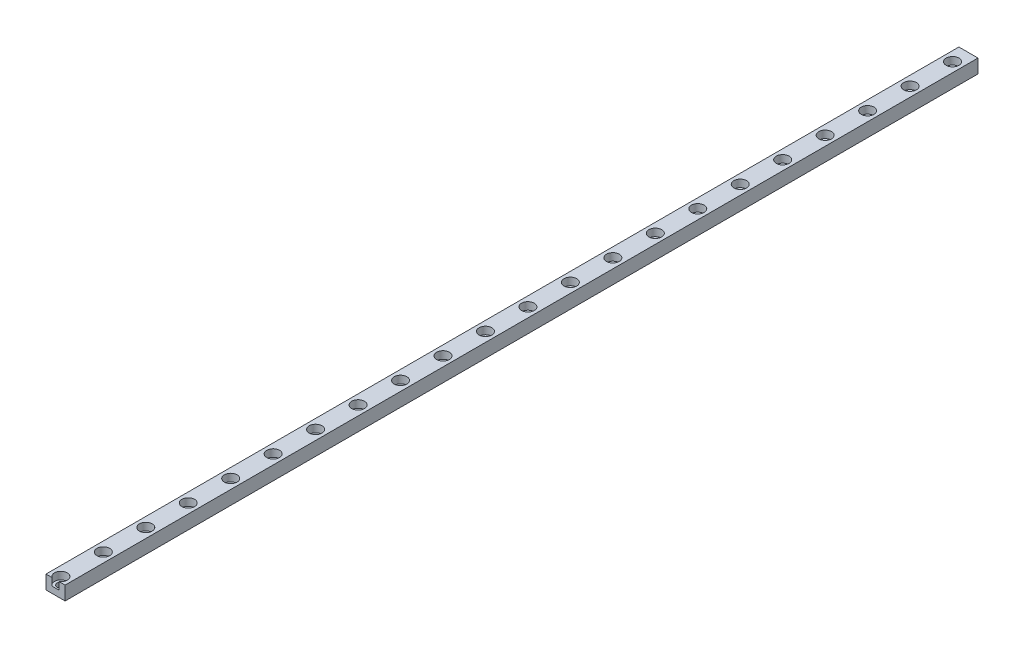
SolidWorks part; units mm, degrees
material "AISI 304"
ref_plane "前视基准面" through (0, 0, 0) normal (0, 0, 1) x (1, 0, 0)
ref_plane "上视基准面" through (0, 0, 0) normal (0, 1, 0) x (1, 0, 0)
ref_plane "右视基准面" through (0, 0, 0) normal (1, 0, 0) x (0, 0, -1)
sketch "草图1" plane through (0, 0, -89.2648) normal (0, 0, 1) x (1, 0, 0)
  line L1 (-4.5, -3.25) -> (4.5, -3.25)
  line L2 (-4.5, -3.25) -> (-4.5, 3.25)
  line L3 (-4.5, 3.25) -> (4.5, 3.25)
  line L4 (4.5, -3.25) -> (4.5, 3.25)
  line L5 (-4.5, -3.25) -> (4.5, 3.25) construction
  line L6 (-4.5, 3.25) -> (4.5, -3.25) construction
  point P0 (0, 0)
  dimension "D1" = 9
  dimension "D2" = 6.5
extrude "凸台-拉伸1" add sketch "草图1" along normal blind 430
sketch "草图2" plane through (0, 3.25, 0) normal (0, 1, 0) x (1, 0, 0)
  line L0 (0, 0) -> (0, -499.5684) construction
  line L1 (4.5, 89.2648) -> (-4.5, 89.2648) construction
  circle A0 centre (0, 81.7648) radius 1.75
  circle A1 centre (0, 61.7648) radius 1.75
  circle A2 centre (0, 41.7648) radius 1.75
  circle A3 centre (0, 21.7648) radius 1.75
  circle A4 centre (0, 1.7648) radius 1.75
  circle A5 centre (0, -18.2352) radius 1.75
  circle A6 centre (0, -38.2352) radius 1.75
  circle A7 centre (0, -58.2352) radius 1.75
  circle A8 centre (0, -78.2352) radius 1.75
  circle A9 centre (0, -98.2352) radius 1.75
  circle A10 centre (0, -118.2352) radius 1.75
  circle A11 centre (0, -138.2352) radius 1.75
  circle A12 centre (0, -158.2352) radius 1.75
  circle A13 centre (0, -178.2352) radius 1.75
  circle A14 centre (0, -198.2352) radius 1.75
  circle A15 centre (0, -218.2352) radius 1.75
  circle A16 centre (0, -238.2352) radius 1.75
  circle A17 centre (0, -258.2352) radius 1.75
  circle A18 centre (0, -278.2352) radius 1.75
  circle A19 centre (0, -298.2352) radius 1.75
  circle A20 centre (0, -318.2352) radius 1.75
  circle A21 centre (0, -338.2352) radius 1.75
  circle A22 centre (0, -358.2352) radius 1.75
  circle A23 centre (0, -378.2352) radius 1.75
  circle A24 centre (0, -398.2352) radius 1.75
  circle A25 centre (0, -418.2352) radius 1.75
  circle A26 centre (0, -438.2352) radius 1.75
  circle A27 centre (0, -458.2352) radius 1.75
  circle A28 centre (0, -478.2352) radius 1.75
  circle A29 centre (0, -498.2352) radius 1.75
  circle A30 centre (0, -518.2352) radius 1.75
  circle A31 centre (0, -538.2352) radius 1.75
  circle A32 centre (0, -558.2352) radius 1.75
  circle A33 centre (0, -578.2352) radius 1.75
  circle A34 centre (0, -598.2352) radius 1.75
  circle A35 centre (0, -618.2352) radius 1.75
  circle A36 centre (0, -638.2352) radius 1.75
  circle A37 centre (0, -658.2352) radius 1.75
  circle A38 centre (0, -678.2352) radius 1.75
  circle A39 centre (0, -698.2352) radius 1.75
  circle A40 centre (0, -718.2352) radius 1.75
  circle A41 centre (0, -738.2352) radius 1.75
  circle A42 centre (0, -758.2352) radius 1.75
  circle A43 centre (0, -778.2352) radius 1.75
  circle A44 centre (0, -798.2352) radius 1.75
  circle A45 centre (0, -818.2352) radius 1.75
  circle A46 centre (0, -838.2352) radius 1.75
  circle A47 centre (0, -858.2352) radius 1.75
  circle A48 centre (0, -878.2352) radius 1.75
  circle A49 centre (0, -898.2352) radius 1.75
  circle A50 centre (0, -918.2352) radius 1.75
  circle A51 centre (0, -938.2352) radius 1.75
  circle A52 centre (0, -958.2352) radius 1.75
  circle A53 centre (0, -978.2352) radius 1.75
  circle A54 centre (0, -998.2352) radius 1.75
  circle A55 centre (0, -1018.2352) radius 1.75
  circle A56 centre (0, -1038.2352) radius 1.75
  circle A57 centre (0, -1058.2352) radius 1.75
  circle A58 centre (0, -1078.2352) radius 1.75
  circle A59 centre (0, -1098.2352) radius 1.75
  dimension "D1" = 3.5
  dimension "D2" = 7.5
  dimension "D4" = 20
  dimension "D3" = 60
extrude "切除-拉伸1" cut sketch "草图2" against normal through all
sketch "草图3" plane through (0, 3.25, 0) normal (0, 1, 0) x (1, 0, 0)
  circle A0 centre (0, 81.7648) radius 3
  circle A1 centre (0, 61.7648) radius 3
  circle A2 centre (0, 41.7648) radius 3
  circle A3 centre (0, 21.7648) radius 3
  circle A4 centre (0, 1.7648) radius 3
  circle A5 centre (0, -18.2352) radius 3
  circle A6 centre (0, -38.2352) radius 3
  circle A7 centre (0, -58.2352) radius 3
  circle A8 centre (0, -78.2352) radius 3
  circle A9 centre (0, -98.2352) radius 3
  circle A10 centre (0, -118.2352) radius 3
  circle A11 centre (0, -138.2352) radius 3
  circle A12 centre (0, -158.2352) radius 3
  circle A13 centre (0, -178.2352) radius 3
  circle A14 centre (0, -198.2352) radius 3
  circle A15 centre (0, -218.2352) radius 3
  circle A16 centre (0, -238.2352) radius 3
  circle A17 centre (0, -258.2352) radius 3
  circle A18 centre (0, -278.2352) radius 3
  circle A19 centre (0, -298.2352) radius 3
  circle A20 centre (0, -318.2352) radius 3
  circle A21 centre (0, -338.2352) radius 3
  circle A22 centre (0, -358.2352) radius 3
  circle A23 centre (0, -378.2352) radius 3
  circle A24 centre (0, -398.2352) radius 3
  circle A25 centre (0, -418.2352) radius 3
  circle A26 centre (0, -438.2352) radius 3
  circle A27 centre (0, -458.2352) radius 3
  circle A28 centre (0, -478.2352) radius 3
  circle A29 centre (0, -498.2352) radius 3
  circle A30 centre (0, -518.2352) radius 3
  circle A31 centre (0, -538.2352) radius 3
  circle A32 centre (0, -558.2352) radius 3
  circle A33 centre (0, -578.2352) radius 3
  circle A34 centre (0, -598.2352) radius 3
  circle A35 centre (0, -618.2352) radius 3
  circle A36 centre (0, -638.2352) radius 3
  circle A37 centre (0, -658.2352) radius 3
  circle A38 centre (0, -678.2352) radius 3
  circle A39 centre (0, -698.2352) radius 3
  circle A40 centre (0, -718.2352) radius 3
  circle A41 centre (0, -738.2352) radius 3
  circle A42 centre (0, -758.2352) radius 3
  circle A43 centre (0, -778.2352) radius 3
  circle A44 centre (0, -798.2352) radius 3
  circle A45 centre (0, -818.2352) radius 3
  circle A46 centre (0, -838.2352) radius 3
  circle A47 centre (0, -858.2352) radius 3
  circle A48 centre (0, -878.2352) radius 3
  circle A49 centre (0, -898.2352) radius 3
  circle A50 centre (0, -918.2352) radius 3
  circle A51 centre (0, -938.2352) radius 3
  circle A52 centre (0, -958.2352) radius 3
  circle A53 centre (0, -978.2352) radius 3
  circle A54 centre (0, -998.2352) radius 3
  circle A55 centre (0, -1018.2352) radius 3
  circle A56 centre (0, -1038.2352) radius 3
  circle A57 centre (0, -1058.2352) radius 3
  circle A58 centre (0, -1078.2352) radius 3
  circle A59 centre (0, -1098.2352) radius 3
  dimension "D1" = 6
  dimension "D3" = 20
  dimension "D2" = 60
extrude "切除-拉伸2" cut sketch "草图3" against normal blind 3.5
